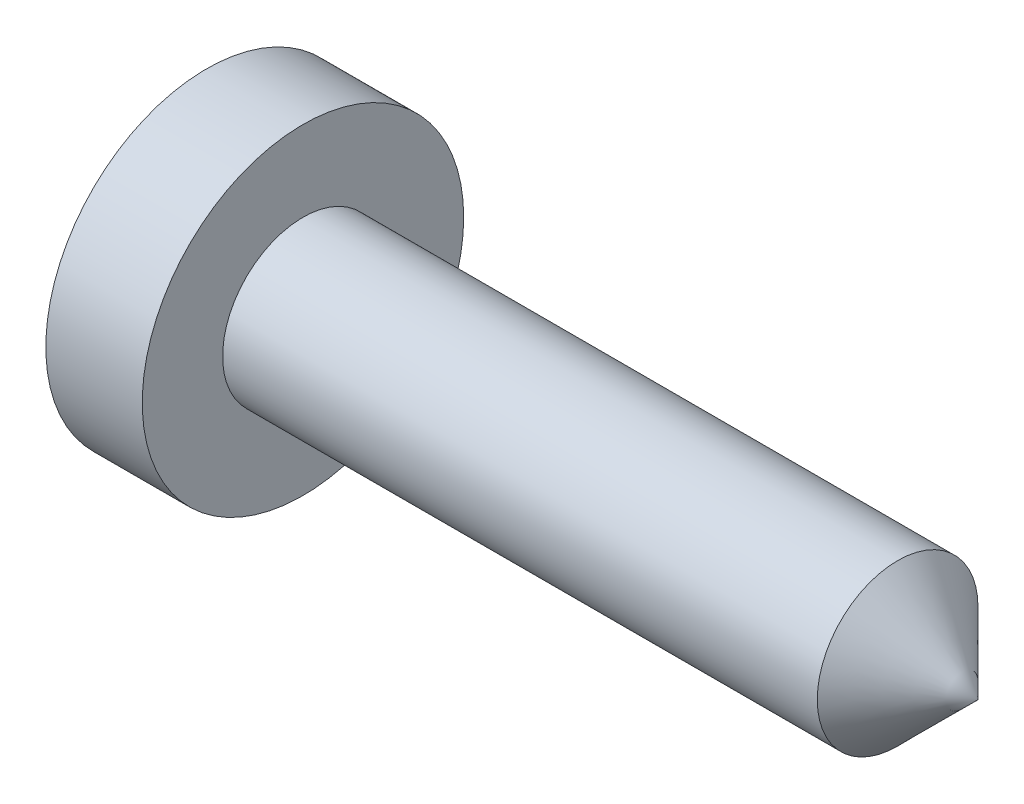
SolidWorks part; units mm, degrees
ref_plane "Front Plane" through (0, 0, 0) normal (0, 0, 1) x (1, 0, 0)
ref_plane "Top Plane" through (0, 0, 0) normal (0, 1, 0) x (1, 0, 0)
ref_plane "Right Plane" through (0, 0, 0) normal (1, 0, 0) x (0, 0, -1)
sketch "Sketch1" plane through (0, 0, 0) normal (1, 0, 0) x (0, 0, -1)
  circle A0 centre (0, 0) radius 5
  dimension "D1" = 10
extrude "Boss-Extrude1" add sketch "Sketch1" along normal blind 3
sketch "Sketch3" plane through (3, 0, 0) normal (1, 0, 0) x (0, 0, -1)
  circle A0 centre (0, 0) radius 2.5
  dimension "D1" = 5
extrude "Boss-Extrude2" add sketch "Sketch3" along normal blind 18.5
sketch "Sketch4" plane through (0, 0, 0) normal (0, 0, 1) x (1, 0, 0)
  line L0 (21.5, 0) -> (24, 0)
  line L1 (21.5, -2.5) -> (21.5, 2.5) construction
  line L2 (24, 0) -> (21.5, 2.5)
  line L3 (21.5, 2.5) -> (21.5, 0)
  dimension "D1" = 2.5
revolve "Revolve1" add sketch "Sketch4" angle 360 about L0
